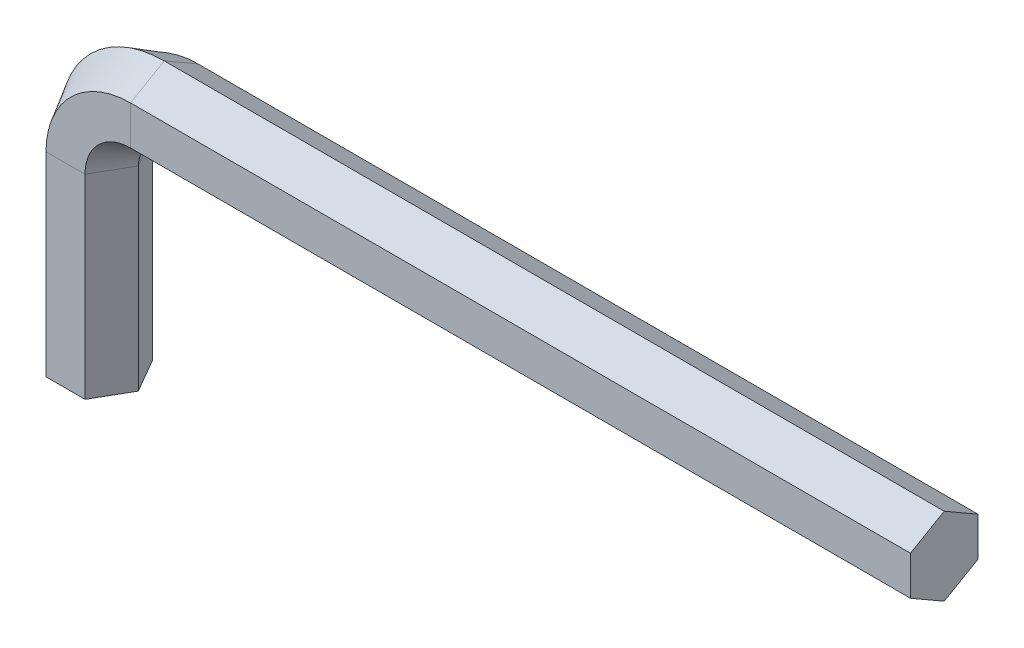
SolidWorks part; units mm, degrees
ref_plane "Front Plane" through (0, 0, 0) normal (0, 0, 1) x (1, 0, 0)
ref_plane "Top Plane" through (0, 0, 0) normal (0, 1, 0) x (1, 0, 0)
ref_plane "Right Plane" through (0, 0, 0) normal (1, 0, 0) x (0, 0, -1)
sketch "Sketch1" plane through (0, 0, 0) normal (0, 0, 1) x (1, 0, 0)
  line L0 (0, 0) -> (0, 15)
  line L1 (5, 20) -> (65, 20)
  arc A0 (5, 20) -> (0, 15) centre (5, 15) ccw
  point P6 (0, 20)
  dimension "D3" = 5
  dimension "D1" = 20
  dimension "D2" = 65
sketch "Sketch2" plane through (0, 0, 0) normal (0, 1, 0) x (1, 0, 0)
  line L1 (3, 0) -> (1.5, 2.5981)
  line L2 (1.5, 2.5981) -> (-1.5, 2.5981)
  line L3 (-1.5, 2.5981) -> (-3, 0)
  line L4 (-3, 0) -> (-1.5, -2.5981)
  line L5 (-1.5, -2.5981) -> (1.5, -2.5981)
  line L6 (1.5, -2.5981) -> (3, 0)
  circle A0 centre (0, 0) radius 2.5981 construction
  dimension "D1" = 3
sweep "Sweep1" add profiles "Sketch2" path "Sketch1"
